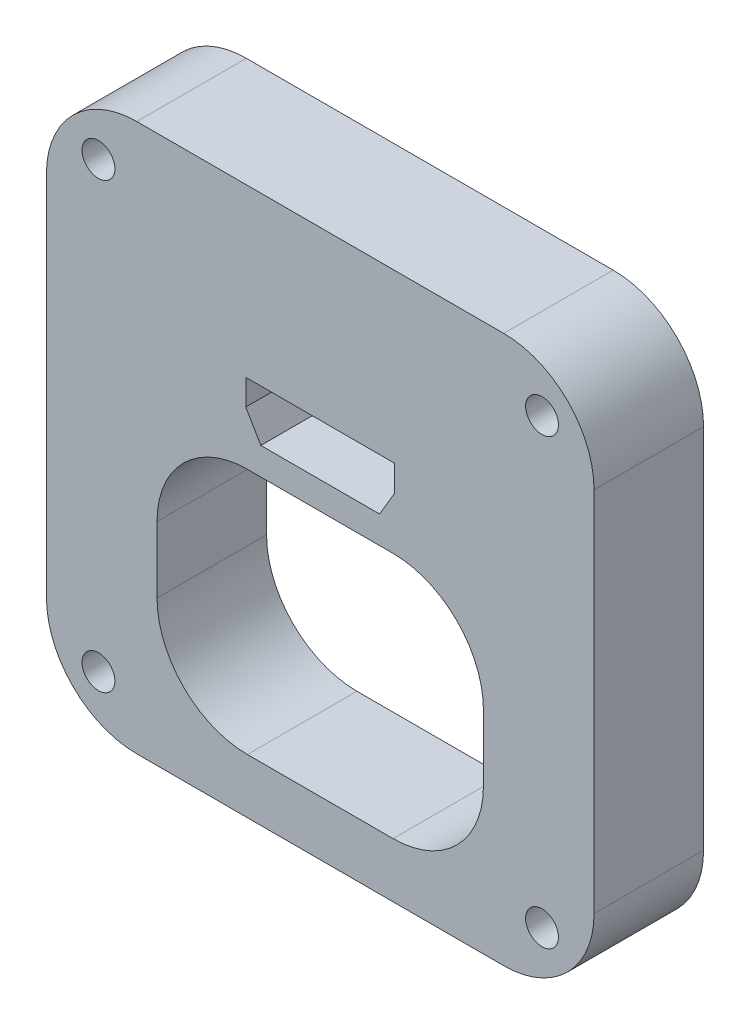
SolidWorks part; units mm, degrees
ref_plane "Front Plane" through (0, 0, 0) normal (0, 0, 1) x (1, 0, 0)
ref_plane "Top Plane" through (0, 0, 0) normal (0, 1, 0) x (1, 0, 0)
ref_plane "Right Plane" through (0, 0, 0) normal (1, 0, 0) x (0, 0, -1)
sketch "Sketch1" plane through (0, 0, 0) normal (0, 0, 1) x (1, 0, 0)
  line L1 (-8.509, -12.7) -> (8.509, -12.7)
  line L2 (-12.7, -8.509) -> (-12.7, 8.509)
  line L3 (-8.509, 12.7) -> (8.509, 12.7)
  line L4 (12.7, -8.509) -> (12.7, 8.509)
  line L5 (-12.7, -12.7) -> (12.7, 12.7) construction
  line L6 (-12.7, 12.7) -> (12.7, -12.7) construction
  arc A0 (8.509, 12.7) -> (12.7, 8.509) centre (8.509, 8.509) cw
  arc A1 (12.7, -8.509) -> (8.509, -12.7) centre (8.509, -8.509) cw
  arc A2 (-8.509, -12.7) -> (-12.7, -8.509) centre (-8.509, -8.509) cw
  arc A3 (-12.7, 8.509) -> (-8.509, 12.7) centre (-8.509, 8.509) cw
  point P0 (0, 0)
  dimension "D3" = 4.191
  dimension "D1" = 25.4
  dimension "D2" = 25.4
extrude "Boss-Extrude1" add sketch "Sketch1" along normal blind 5.08
sketch "Sketch2" plane through (0, 0, 0) normal (0, 0, -1) x (-1, 0, 0)
  line L0 (0, -12.7) -> (0, -10.16) construction
  line L1 (8.509, -12.7) -> (-8.509, -12.7) construction
  line L2 (0, -10.16) -> (0, 1.2954) construction
  line L3 (7.5692, -4.4323) -> (-7.5692, -4.4323) construction
  line L5 (-3.3782, 1.2954) -> (3.3782, 1.2954)
  line L6 (7.5692, -2.8956) -> (7.5692, -5.969)
  line L7 (3.3782, -10.16) -> (-3.3782, -10.16)
  line L9 (-7.5692, -2.8956) -> (-7.5692, -5.969)
  line L10 (0, 1.2954) -> (0, 2.5654)
  line L11 (2.7559, 2.5654) -> (-2.7559, 2.5654)
  line L12 (0, 2.5654) -> (0, 4.953)
  line L13 (3.4544, 4.953) -> (-3.4544, 4.953)
  line L14 (-3.4544, 4.953) -> (-3.4544, 3.7592)
  line L15 (3.4544, 4.953) -> (3.4544, 3.7592)
  line L16 (-3.4544, 3.7592) -> (-2.7559, 2.5654)
  line L17 (3.4544, 3.7592) -> (2.7559, 2.5654)
  arc A0 (7.5692, -2.8956) -> (3.3782, 1.2954) centre (3.3782, -2.8956) ccw
  arc A1 (7.5692, -5.969) -> (3.3782, -10.16) centre (3.3782, -5.969) cw
  arc A2 (-3.3782, -10.16) -> (-7.5692, -5.969) centre (-3.3782, -5.969) cw
  arc A3 (-7.5692, -2.8956) -> (-3.3782, 1.2954) centre (-3.3782, -2.8956) cw
  point P9 (0, -4.4323)
  point P25 (0, 2.5654)
  point P29 (0, 4.953)
  dimension "D4" = 4.191
  dimension "D1" = 2.54
  dimension "D2" = 11.4554
  dimension "D3" = 15.1384
  dimension "D5" = 1.27
  dimension "D6" = 5.5118
  dimension "D7" = 2.3876
  dimension "D8" = 6.9088
  dimension "D9" = 1.1938
  dimension "D10" = 1.1938
extrude "Cut-Extrude1" cut sketch "Sketch2" against normal blind 5.08 contours L14 L16 L11 L12 L13 | L17 L15 L13 L12 L11 | A3 L9 A2 L7 A1 L6 A0 L5
sketch "Sketch3" plane through (0, 0, 0) normal (0, 0, -1) x (-1, 0, 0)
  line L0 (-8.509, 12.7) -> (-8.509, 8.509)
  line L1 (-8.509, 8.509) -> (-12.7, 8.509)
  line L2 (-10.287, 10.287) -> (-8.509, 10.287)
  line L3 (-10.287, 10.287) -> (-10.287, 8.509)
  line L4 (0, 12.7) -> (0, -12.7) construction
  line L5 (-8.509, 12.7) -> (8.509, 12.7) construction
  line L6 (8.509, -12.7) -> (-8.509, -12.7) construction
  line L7 (-12.7, 0) -> (12.7, 0) construction
  line L8 (-12.7, -8.509) -> (-12.7, 8.509) construction
  line L9 (12.7, 8.509) -> (12.7, -8.509) construction
  circle A0 centre (-10.287, 10.287) radius 0.762
  circle A1 centre (-10.287, -10.287) radius 0.762
  circle A2 centre (10.287, -10.287) radius 0.762
  circle A3 centre (10.287, 10.287) radius 0.762
  dimension "D1" = 1.524
  dimension "D2" = 1.778
  dimension "D3" = 1.778
extrude "Cut-Extrude2" cut sketch "Sketch3" against normal blind 5.08 contours A2 | A1 | A0 | A3
